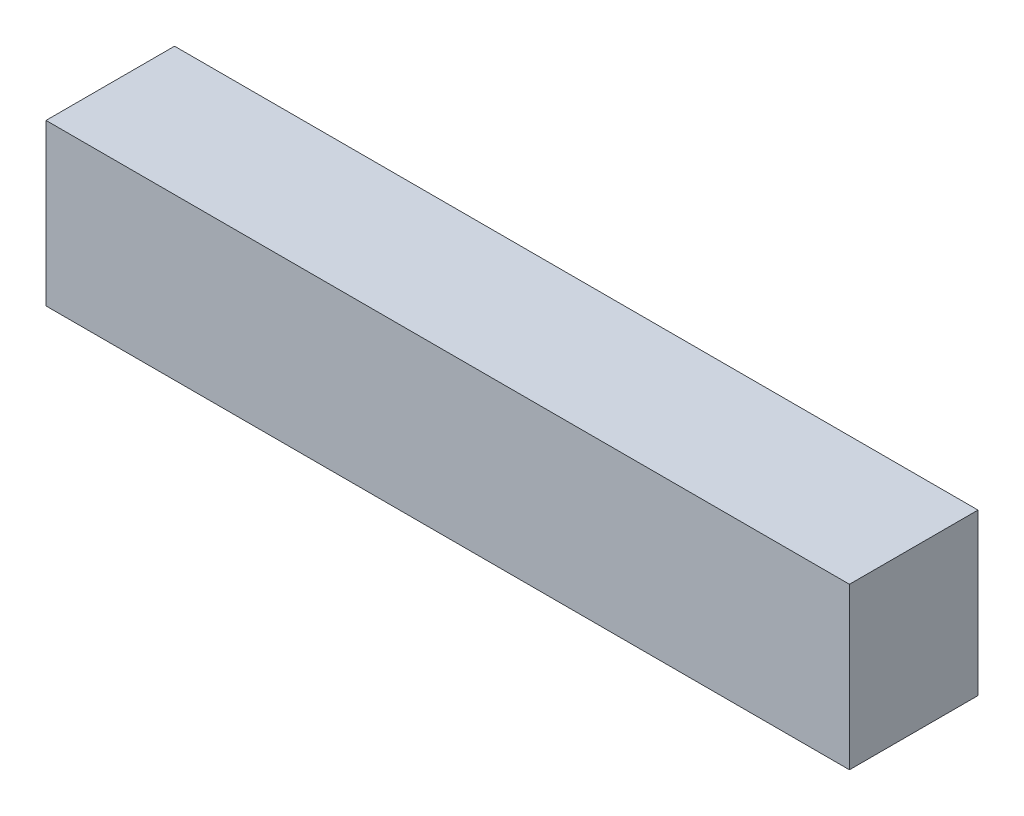
SolidWorks part; units mm, degrees
ref_plane "Front Plane" through (0, 0, 0) normal (0, 0, 1) x (1, 0, 0)
ref_plane "Top Plane" through (0, 0, 0) normal (0, 1, 0) x (1, 0, 0)
ref_plane "Right Plane" through (0, 0, 0) normal (1, 0, 0) x (0, 0, -1)
sketch "Sketch1" plane through (0, 0, 0) normal (0, 0, 1) x (1, 0, 0)
  line L0 (0, 5) -> (50, 5) construction
  line L1 (0, 0) -> (50, 0)
  line L2 (0, 0) -> (0, 10)
  line L3 (0, 10) -> (50, 10)
  line L4 (50, 0) -> (50, 10)
  line L5 (25, 10) -> (25, 0) construction
  circle A0 centre (5.5, 5) radius 1.5
  circle A2 centre (44.5, 5) radius 1.5
  point P13 (5.2949, 5)
  dimension "D2" = 3
  dimension "D3" = 39
  dimension "D1" = 50
  dimension "D5" = 10
extrude "Boss-Extrude2" add sketch "Sketch1" along normal blind 6 contours L3 L4 L1 L2 | A2 | A0
sketch "Sketch2" plane through (0, 0, 6) normal (0, 0, 1) x (1, 0, 0)
  line L1 (0, 0) -> (50, 0)
  line L2 (0, 0) -> (0, 10)
  line L3 (0, 10) -> (50, 10)
  line L4 (50, 0) -> (50, 10)
extrude "Boss-Extrude3" add sketch "Sketch2" along normal blind 2
